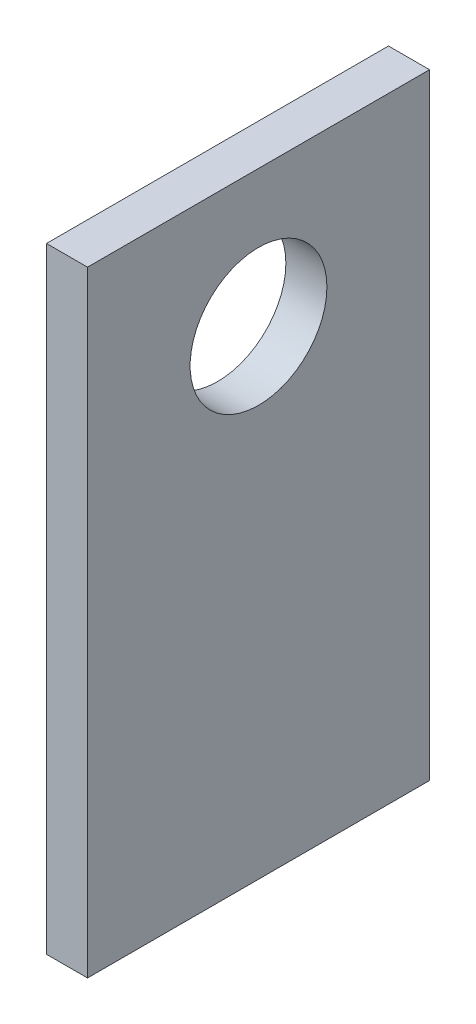
SolidWorks part; units mm, degrees
material "Perspex (TM) GS Acrylic Cast Sheet"
ref_plane "Front Plane" through (0, 0, 0) normal (0, 0, 1) x (1, 0, 0)
ref_plane "Top Plane" through (0, 0, 0) normal (0, 1, 0) x (1, 0, 0)
ref_plane "Right Plane" through (0, 0, 0) normal (1, 0, 0) x (0, 0, -1)
sketch "Sketch1" plane through (0, 0, 0) normal (1, 0, 0) x (0, 0, -1)
  line L2 (-12.5, -22.5) -> (12.5, -22.5)
  line L3 (-12.5, -22.5) -> (-12.5, 22.5)
  line L4 (-12.5, 22.5) -> (12.5, 22.5)
  line L5 (12.5, -22.5) -> (12.5, 22.5)
  line L6 (-12.5, -22.5) -> (12.5, 22.5) construction
  line L7 (-12.5, 22.5) -> (12.5, -22.5) construction
  point P0 (0, -22.5)
  point P1 (0, 0)
  dimension "D1" = 45
  dimension "D2" = 25
extrude "Boss-Extrude1" add sketch "Sketch1" along normal blind 3
sketch "Sketch2" plane through (3, 0, 0) normal (1, 0, 0) x (0, 0, -1)
  line L0 (-12.5, -22.5) -> (12.5, -22.5) construction
  line L1 (-12.5, 22.5) -> (-12.5, -22.5) construction
  circle A0 centre (0, 12.5) radius 5
  dimension "D1" = 10
  dimension "D2" = 35
  dimension "D3" = 12.5
extrude "Cut-Extrude1" cut sketch "Sketch2" against normal blind 3
